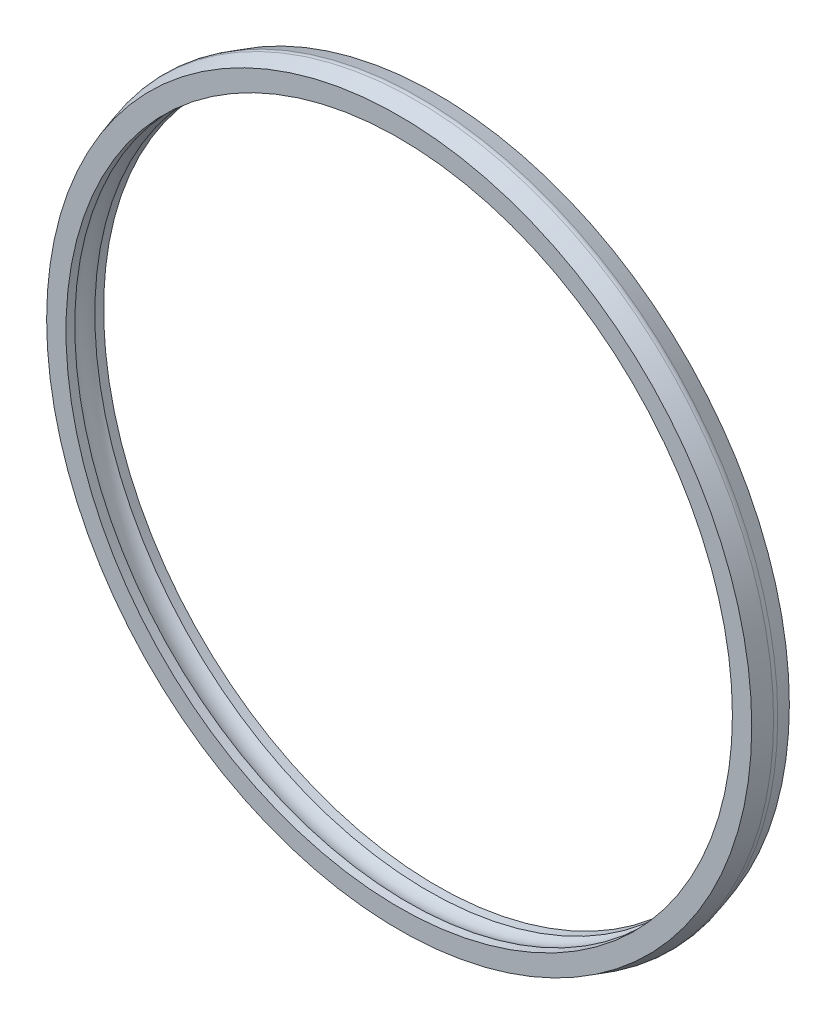
SolidWorks part; units mm, degrees
material "95 AU V142"
ref_plane "Front Plane" through (0, 0, 0) normal (0, 0, 1) x (1, 0, 0)
ref_plane "Top Plane" through (0, 0, 0) normal (0, 1, 0) x (1, 0, 0)
ref_plane "Right Plane" through (0, 0, 0) normal (1, 0, 0) x (0, 0, -1)
sketch "Sketch1" plane through (0, 0, 0) normal (1, 0, 0) x (0, 0, -1)
  line L0 (0, 0) -> (65.0135, 0) construction
  line L1 (0, 0) -> (0, 77.6931) construction
  line L2 (0.2915, 49.9112) -> (2.625, 49.2)
  line L3 (2.625, 49.2) -> (2.625, 46.5)
  line L4 (2.625, 46.5) -> (1.4, 46.5)
  line L5 (-2.625, 46.5) -> (-1.4, 46.5)
  line L6 (-2.625, 49.2) -> (-2.625, 46.5)
  line L7 (-0.2915, 49.9112) -> (-2.625, 49.2)
  arc A0 (-1.4, 46.5) -> (1.4, 46.5) centre (0, 43.8467) cw
  arc A1 (0.2915, 49.9112) -> (-0.2915, 49.9112) centre (0, 48.9546) ccw
  point P14 (0, 50)
  dimension "D2" = 3.5
  dimension "D3" = 3
  dimension "D7" = 1
  dimension "D1" = 5.25
  dimension "D4" = 2.8
  dimension "D5" = 2.7
  dimension "D6" = 93
  dimension "D8" = 100
revolve "Revolve1" add sketch "Sketch1" angle 360 about L0
